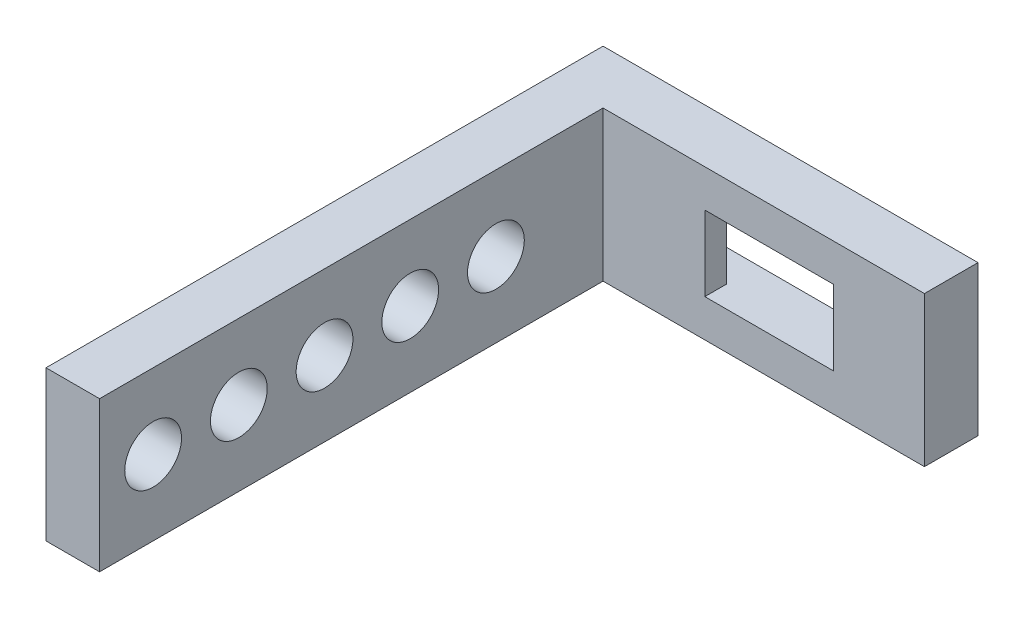
SolidWorks part; units mm, degrees
ref_plane "Front Plane" through (0, 0, 0) normal (0, 0, 1) x (1, 0, 0)
ref_plane "Top Plane" through (0, 0, 0) normal (0, 1, 0) x (1, 0, 0)
ref_plane "Right Plane" through (0, 0, 0) normal (1, 0, 0) x (0, 0, -1)
sketch "Sketch1" plane through (0, 0, 0) normal (0, 1, 0) x (1, 0, 0)
  line L2 (6.5891, 0) -> (10, 0)
  line L8 (0, 9) -> (11.5891, 9)
  line L10 (11.5891, 9) -> (40, 9)
  line L11 (40, 9) -> (40, 4)
  line L13 (6.5891, 0) -> (0, 0)
  line L15 (0, 0) -> (0, 9)
  line L17 (0, 0) -> (37.5449, 0) construction
  line L18 (10, 0) -> (10, 4)
  line L19 (10, 4) -> (40, 4)
  line L20 (25, 4) -> (25, 9) construction
  dimension "D2" = 25
  dimension "D4" = 30
  dimension "D9" = 5
  dimension "D10" = 4
extrude "Boss-Extrude1" add sketch "Sketch1" along normal blind 14
sketch "Sketch2" plane through (0, 0, -4) normal (0, 0, 1) x (1, 0, 0)
  line L0 (40, 7) -> (10, 7) construction
  line L1 (37.5, 3.5) -> (12.5, 3.5)
  line L2 (37.5, 3.5) -> (37.5, 10.5)
  line L3 (37.5, 10.5) -> (12.5, 10.5)
  line L4 (12.5, 3.5) -> (12.5, 10.5)
  line L6 (40, 14) -> (40, 0) construction
  line L7 (25, 3.5) -> (25, 10.5) construction
  line L8 (10, 14) -> (10, 0) construction
  line L11 (37.5, 7) -> (12.5, 7) construction
  line L14 (25, 14) -> (25, 0) construction
  line L15 (10, 14) -> (40, 14) construction
  line L16 (10, 0) -> (40, 0) construction
  dimension "D1" = 25
  dimension "D2" = 7
extrude "Cut-Extrude3" [suppressed] cut sketch "Sketch2" against normal blind 3
sketch "Sketch10" [suppressed] plane through (0, 0, -7) normal (0, 0, 1) x (1, 0, 0)
  line L0 (25, 10.5) -> (25, 3.5) construction
  line L1 (34, 9.5) -> (16, 9.5)
  line L2 (34, 9.5) -> (34, 4.5)
  line L3 (34, 4.5) -> (16, 4.5)
  line L4 (16, 9.5) -> (16, 4.5)
  line L5 (34, 9.5) -> (16, 4.5) construction
  line L6 (34, 4.5) -> (16, 9.5) construction
  line L7 (37.5, 10.5) -> (12.5, 10.5) construction
  line L8 (12.5, 3.5) -> (37.5, 3.5) construction
  line L9 (12.5, 7) -> (37.5, 7) construction
  line L10 (12.5, 10.5) -> (12.5, 3.5) construction
  line L11 (37.5, 3.5) -> (37.5, 10.5) construction
  point P0 (25, 7)
  point P11 (25, 9.5)
  point P18 (16, 7)
  dimension "D1" = 18
  dimension "D2" = 5
extrude "Cut-Extrude4" [suppressed] cut sketch "Sketch10" against normal through all
sketch "Sketch11" plane through (0, 0, 0) normal (-1, 0, 0) x (0, 0, 1)
  line L7 (-9, 14) -> (0, 14) construction
  line L12 (-5, 14) -> (-5, 24)
  line L18 (0, 14) -> (0, 15)
  line L20 (-5, 14) -> (0, 14)
  line L23 (-5, 24) -> (-2.8009, 24)
  line L24 (-2.8009, 24) -> (-2.8009, 15)
  line L25 (-2.8009, 15) -> (0, 15)
  dimension "D1" = 9
  dimension "D2" = 5
  dimension "D3" = 10
extrude "Boss-Extrude8" [suppressed] add sketch "Sketch11" against normal blind 3
sketch "Sketch12" [suppressed] plane through (3, 0, 0) normal (1, 0, 0) x (0, 0, -1)
  line L0 (2.8009, 15) -> (2.8009, 24) construction
  line L1 (8.4206, 15) -> (2.8009, 15) construction
  circle A0 centre (5.3009, 17.5) radius 2.5
  dimension "D1" = 5
extrude "Boss-Extrude9" [suppressed] add sketch "Sketch12" along normal blind 9
ref_plane "Plane1" through (10, 0, 0) normal (-1, 0, 0) x (0, 0, 1)
sketch "Sketch14" [suppressed] plane through (0, 0, -17.4206) normal (0, 0, -1) x (-1, 0, 0)
  line L0 (-59, 0) -> (0, 0) construction
  line L1 (-10, 0) -> (-3, 0)
  line L2 (-10, 0) -> (-10, 12)
  line L3 (-10, 12) -> (-3, 12)
  line L4 (-3, 0) -> (-3, 12)
  line L5 (-3, 24) -> (-3, 14) construction
  dimension "D1" = 12
  dimension "D2" = 7
sketch "Sketch15" [suppressed] plane through (0, 0, 0) normal (-1, 0, 0) x (0, 0, 1)
  line L1 (-8.1108, 24) -> (-8.1108, 15.2416) construction
  line L2 (-2.8009, 24) -> (-13.4206, 24) construction
  line L3 (-2.8009, 19.5) -> (-12.1862, 19.5) construction
  line L4 (-2.8009, 15) -> (-2.8009, 24) construction
  circle A0 centre (-8.1108, 19.5) radius 2.5
  dimension "D1" = 5
extrude "Cut-Extrude8" [suppressed] cut sketch "Sketch15" against normal through all
sketch "Sketch16" [suppressed] plane through (0, 0, -17.4206) normal (0, 0, -1) x (-1, 0, 0)
  line L0 (-59, 0) -> (0, 0) construction
  line L1 (-15, 11) -> (-3, 11)
  line L2 (-15, 11) -> (-15, 0)
  line L3 (-15, 0) -> (-3, 0)
  line L4 (-3, 11) -> (-3, 0)
  line L5 (-3, 24) -> (-3, 14) construction
  dimension "D1" = 12
  dimension "D2" = 11
extrude "Cut-Extrude9" [suppressed] cut sketch "Sketch16" against normal blind 9
sketch "Sketch19" [suppressed] plane through (0, 0, -17.4206) normal (0, 0, -1) x (-1, 0, 0)
  line L0 (-59, 0) -> (0, 0) construction
  line L1 (-13.7627, 0) -> (-3, 0)
  line L2 (-13.7627, 0) -> (-13.7627, 11.672)
  line L3 (-13.7627, 11.672) -> (-3, 11.672)
  line L4 (-3, 0) -> (-3, 11.672)
  line L5 (-3, 24) -> (-3, 14) construction
extrude "Cut-Extrude12" [suppressed] cut sketch "Sketch19" against normal blind 7
sketch "Sketch20" plane through (0, 0, 0) normal (-1, 0, 0) x (0, 0, 1)
  line L0 (-4, 14) -> (-4, 0) construction
  line L1 (0, 0) -> (43, 0)
  line L2 (0, 0) -> (0, 14)
  line L3 (0, 14) -> (43, 14)
  line L4 (43, 0) -> (43, 14)
  dimension "D1" = 47
extrude "Boss-Extrude10" add sketch "Sketch20" against normal blind 5
sketch "Sketch21" plane through (0, 0, 0) normal (-1, 0, 0) x (0, 0, 1)
  line L0 (-9, 14) -> (-9, 0) construction
  line L1 (-9, 7) -> (43, 7) construction
  line L2 (43, 0) -> (43, 14) construction
  circle A0 centre (-2, 7) radius 2.65
  circle A3 centre (6, 7) radius 2.65
  circle A4 centre (14, 7) radius 2.65
  circle A5 centre (22, 7) radius 2.65
  circle A6 centre (30, 7) radius 2.65
  circle A7 centre (38, 7) radius 2.65
  dimension "D1" = 5.3
  dimension "D2" = 5
  dimension "D3" = 4
  dimension "D4" = 3
extrude "Cut-Extrude13" cut sketch "Sketch21" against normal up to surface (5 mm away) contours A0 | A3 | A4 | A5 | A6 | A7 up to face at (5, 7, 21.5)
sketch "Sketch22" plane through (0, 14, 0) normal (0, 1, 0) x (1, 0, 0)
  line L0 (10, 4.95) -> (10, -4.95) construction
  line L1 (5, 0) -> (10, 0)
  line L2 (5, 0) -> (5, 4)
  line L3 (5, 4) -> (10, 4)
  line L4 (10, 0) -> (10, 4)
  line L5 (10, 4) -> (40, 4) construction
extrude "Cut-Extrude14" cut sketch "Sketch22" against normal through all
sketch "Sketch23" plane through (0, 0, 0) normal (-1, 0, 0) x (0, 0, 1)
  circle A0 centre (-2, 7) radius 2.65
extrude "Boss-Extrude11" add sketch "Sketch23" against normal up to surface (5 mm away) up to face at (5, 7, 12.4417)
sketch "Sketch24" plane through (0, 0, -9) normal (0, 0, -1) x (-1, 0, 0)
  line L0 (0, 7) -> (-40, 7) construction
  line L1 (-8, 10.5) -> (-33, 10.5)
  line L2 (-8, 10.5) -> (-8, 3.5)
  line L3 (-8, 3.5) -> (-33, 3.5)
  line L4 (-33, 10.5) -> (-33, 3.5)
  line L5 (0, 14) -> (0, 0) construction
  line L6 (-40, 14) -> (-40, 0) construction
  point P10 (-8, 7)
  dimension "D1" = 25
  dimension "D2" = 7
  dimension "D3" = 7
extrude "Cut-Extrude15" cut sketch "Sketch24" against normal blind 3
sketch "Sketch25" plane through (0, 0, -6) normal (0, 0, -1) x (-1, 0, 0)
  line L0 (-20.5, 3.5) -> (-20.5, 10.5) construction
  line L1 (-14.5, 10.5) -> (-26.5, 10.5)
  line L2 (-14.5, 10.5) -> (-14.5, 3.5)
  line L3 (-14.5, 3.5) -> (-26.5, 3.5)
  line L4 (-26.5, 10.5) -> (-26.5, 3.5)
  line L5 (-14.5, 10.5) -> (-26.5, 3.5) construction
  line L6 (-14.5, 3.5) -> (-26.5, 10.5) construction
  line L7 (-33, 3.5) -> (-8, 3.5) construction
  line L8 (-8, 10.5) -> (-33, 10.5) construction
  line L9 (-33, 10.5) -> (-33, 3.5) construction
  point P0 (-20.5, 7)
  point P14 (-33, 7)
  point P15 (-26.5, 7)
  dimension "D1" = 12
  dimension "D2" = 7
extrude "Cut-Extrude16" cut sketch "Sketch25" against normal up to next
sketch "Sketch26" plane through (0, 0, -9) normal (0, 0, -1) x (-1, 0, 0)
  line L0 (-40, 14) -> (0, 14) construction
  line L1 (-40, 0) -> (-35, 0)
  line L2 (-40, 0) -> (-40, 14)
  line L3 (-40, 14) -> (-35, 14)
  line L4 (-35, 0) -> (-35, 14)
  line L5 (-33, 10.5) -> (-33, 3.5) construction
  dimension "D1" = 2
extrude "Cut-Extrude17" cut sketch "Sketch26" against normal up to next
